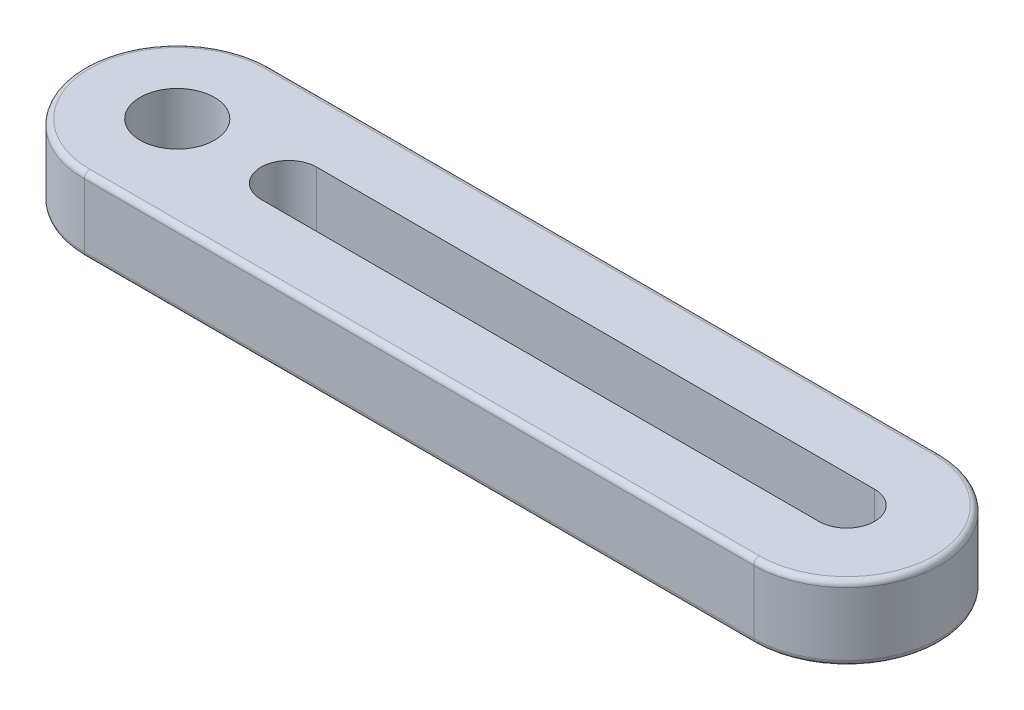
SolidWorks part; units mm, degrees
ref_plane "Front Plane" through (0, 0, 0) normal (0, 0, 1) x (1, 0, 0)
ref_plane "Top Plane" through (0, 0, 0) normal (0, 1, 0) x (1, 0, 0)
ref_plane "Right Plane" through (0, 0, 0) normal (1, 0, 0) x (0, 0, -1)
sketch "Sketch1" plane through (0, 0, 0) normal (0, 1, 0) x (1, 0, 0)
  line L0 (0, 0) -> (180, 0) construction
  line L1 (0, 25) -> (180, 25)
  line L2 (0, -25) -> (180, -25)
  line L3 (30, 0) -> (180, 0) construction
  line L4 (30, 7.5) -> (180, 7.5)
  line L5 (30, -7.5) -> (180, -7.5)
  arc A0 (0, 25) -> (0, -25) centre (0, 0) ccw
  arc A1 (180, -25) -> (180, 25) centre (180, 0) ccw
  circle A2 centre (0, 0) radius 10
  arc A3 (30, 7.5) -> (30, -7.5) centre (30, 0) ccw
  arc A4 (180, -7.5) -> (180, 7.5) centre (180, 0) ccw
  point P3 (90, 0)
  point P12 (105, 0)
  dimension "D1" = 25
  dimension "D3" = 20
  dimension "D2" = 180
  dimension "D4" = 150
  dimension "D5" = 15
extrude "Boss-Extrude1" add sketch "Sketch1" along normal mid plane 20
fillet "Fillet1" radius 1.5 8 edges at (-25, -10, 0) (90, -10, -25) (205, -10, 0) (205, 10, 0) (90, 10, 25) (-25, 10, 0) (90, -10, 25) (90, 10, -25)
